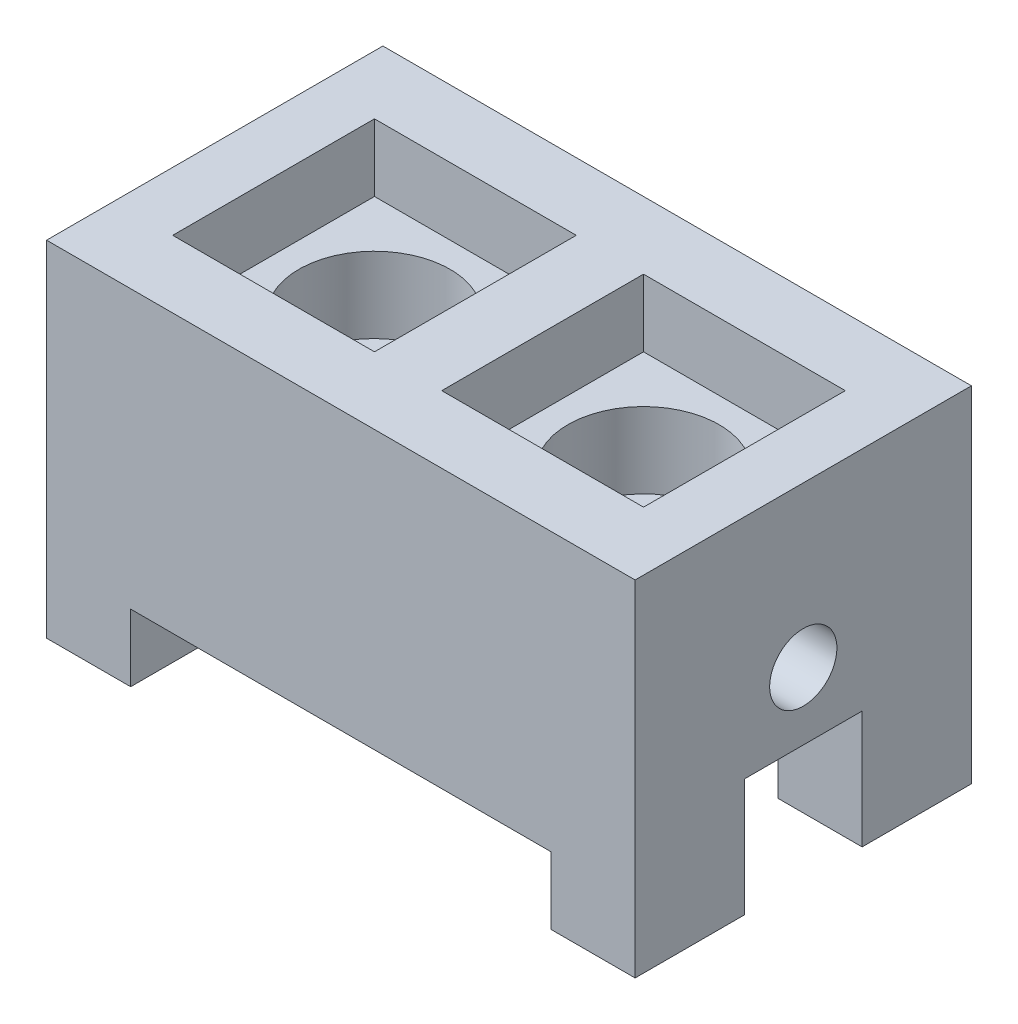
SolidWorks part; units mm, degrees
ref_plane "Front Plane" through (0, 0, 0) normal (0, 0, 1) x (1, 0, 0)
ref_plane "Top Plane" through (0, 0, 0) normal (0, 1, 0) x (1, 0, 0)
ref_plane "Right Plane" through (0, 0, 0) normal (1, 0, 0) x (0, 0, -1)
sketch "Sketch1" plane through (0, 0, 0) normal (0, 0, 1) x (1, 0, 0)
  line L0 (10, 0) -> (10, 8)
  line L13 (0, 0) -> (10, 0)
  line L14 (0, 0) -> (0, 41)
  line L15 (0, 41) -> (70, 41)
  line L16 (70, 0) -> (70, 41)
  line L17 (10, 8) -> (60, 8)
  line L18 (60, 8) -> (60, 0)
  line L19 (60, 0) -> (70, 0)
  dimension "D1" = 70
  dimension "D2" = 41
  dimension "D3" = 50
  dimension "D4" = 10
  dimension "D5" = 8
extrude "Boss-Extrude3" add sketch "Sketch1" along normal blind 40 contours L13 L0 L17 L18 L19 L16 L15 L14
sketch "Sketch7" plane through (70, 0, 0) normal (1, 0, 0) x (0, 0, -1)
  line L1 (-27, 0) -> (-13, 0)
  line L2 (-27, 0) -> (-27, 14)
  line L3 (-27, 14) -> (-13, 14)
  line L4 (0, 0) -> (0, 41)
  line L5 (0, 41) -> (-40, 41)
  line L6 (-40, 41) -> (-40, 0)
  line L7 (-40, 0) -> (0, 0)
  line L8 (0, 0) -> (0, 41)
  line L9 (0, 41) -> (-40, 41)
  line L10 (-40, 41) -> (-40, 0)
  line L11 (-40, 0) -> (0, 0)
  line L12 (-13, 0) -> (-13, 14)
  dimension "D2" = 14
  dimension "D3" = 14
  dimension "D4" = 13
  dimension "D1" = 0
extrude "Cut-Extrude3" cut sketch "Sketch7" against normal blind 108 contours L2 L1 L12 L3
sketch "Sketch8" plane through (70, 0, 0) normal (1, 0, 0) x (0, 0, -1)
  line L8 (-27, 14) -> (-13, 14)
  line L9 (-13, 14) -> (-13, 0)
  line L10 (-13, 0) -> (0, 0)
  line L11 (0, 0) -> (0, 41)
  line L12 (0, 41) -> (-40, 41)
  line L13 (-40, 41) -> (-40, 0)
  line L14 (-40, 0) -> (-27, 0)
  line L15 (-27, 0) -> (-27, 14)
  line L16 (-27, 14) -> (-13, 14)
  line L17 (-13, 14) -> (-13, 0)
  line L18 (-13, 0) -> (0, 0)
  line L19 (0, 0) -> (0, 41)
  line L20 (0, 41) -> (-40, 41)
  line L21 (-40, 41) -> (-40, 0)
  line L22 (-40, 0) -> (-27, 0)
  line L23 (-27, 0) -> (-27, 14)
  circle A0 centre (-20, 22) radius 4
  point P6 (0, 0)
  point P8 (0, 0)
  dimension "D2" = 8
  dimension "D3" = 22
  dimension "D4" = 20
  dimension "D1" = 0
extrude "Cut-Extrude4" cut sketch "Sketch8" against normal blind 108 contours A0
sketch "Sketch9" plane through (0, 41, 0) normal (0, 1, 0) x (1, 0, 0)
  line L1 (7, -8) -> (31, -8)
  line L2 (7, -8) -> (7, -32)
  line L3 (7, -32) -> (31, -32)
  line L4 (70, 0) -> (0, 0)
  line L5 (0, 0) -> (0, -40)
  line L6 (0, -40) -> (70, -40)
  line L7 (70, -40) -> (70, 0)
  line L8 (70, 0) -> (0, 0)
  line L9 (0, 0) -> (0, -40)
  line L10 (0, -40) -> (70, -40)
  line L11 (70, -40) -> (70, 0)
  line L12 (31, -8) -> (31, -32)
  line L13 (39, -8) -> (63, -8)
  line L14 (39, -8) -> (39, -32)
  line L15 (39, -32) -> (63, -32)
  line L16 (63, -8) -> (63, -32)
  dimension "D2" = 24
  dimension "D3" = 24
  dimension "D4" = 24
  dimension "D5" = 24
  dimension "D6" = 8
  dimension "D7" = 7
  dimension "D8" = 8
  dimension "D9" = 8
  dimension "D1" = 0
extrude "Cut-Extrude5" cut sketch "Sketch9" against normal blind 8 contours L2 L1 L12 L3 | L14 L13 L16 L15
sketch "Sketch10" plane through (0, 33, 0) normal (0, 1, 0) x (1, 0, 0)
  line L4 (7, -32) -> (31, -32)
  line L5 (31, -32) -> (31, -8)
  line L6 (31, -8) -> (7, -8)
  line L7 (7, -8) -> (7, -32)
  line L8 (7, -32) -> (31, -32)
  line L9 (31, -32) -> (31, -8)
  line L10 (31, -8) -> (7, -8)
  line L11 (7, -8) -> (7, -32)
  circle A0 centre (19, -20) radius 9
  dimension "D2" = 18
  dimension "D3" = 12
  dimension "D4" = 12
  dimension "D1" = 0
extrude "Cut-Extrude6" cut sketch "Sketch10" against normal blind 9 contours A0
sketch "Sketch11" plane through (0, 33, 0) normal (0, 1, 0) x (1, 0, 0)
  line L4 (39, -32) -> (63, -32)
  line L5 (63, -32) -> (63, -8)
  line L6 (63, -8) -> (39, -8)
  line L7 (39, -8) -> (39, -32)
  line L8 (39, -32) -> (63, -32)
  line L9 (63, -32) -> (63, -8)
  line L10 (63, -8) -> (39, -8)
  line L11 (39, -8) -> (39, -32)
  circle A0 centre (51, -20) radius 9
  point P6 (0, 0)
  point P9 (69.2258, -32.5566)
  dimension "D2" = 18
  dimension "D3" = 12
  dimension "D4" = 12
  dimension "D1" = 0
extrude "Cut-Extrude7" cut sketch "Sketch11" against normal blind 9 contours A0
